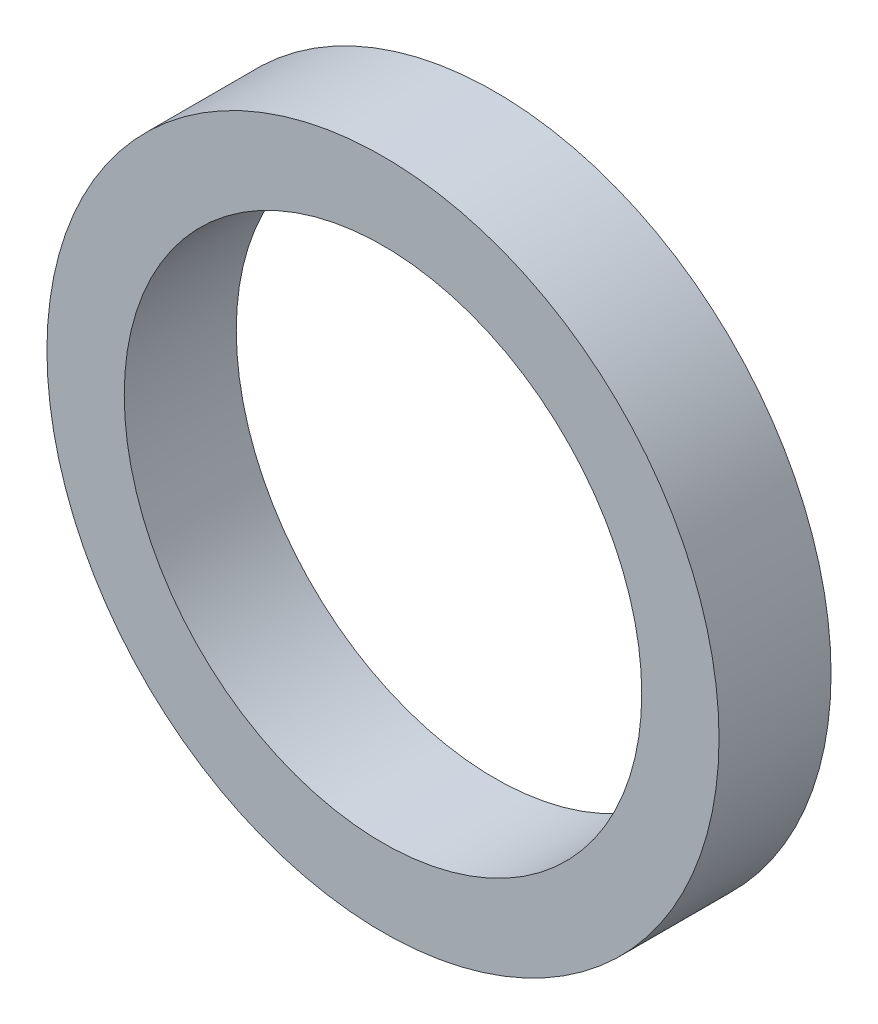
SolidWorks part; units mm, degrees
material "硅橡胶"
ref_plane "前视基准面" through (0, 0, 0) normal (0, 0, 1) x (1, 0, 0)
ref_plane "上视基准面" through (0, 0, 0) normal (0, 1, 0) x (1, 0, 0)
ref_plane "右视基准面" through (0, 0, 0) normal (1, 0, 0) x (0, 0, -1)
sketch "草图1" plane through (0, 0, 0) normal (0, 0, 1) x (1, 0, 0)
  circle A0 centre (0, 0) radius 30
  circle A1 centre (0, 0) radius 23.1
  dimension "D1" = 60
  dimension "D2" = 46.2
extrude "凸台-拉伸1" add sketch "草图1" along normal blind 10
